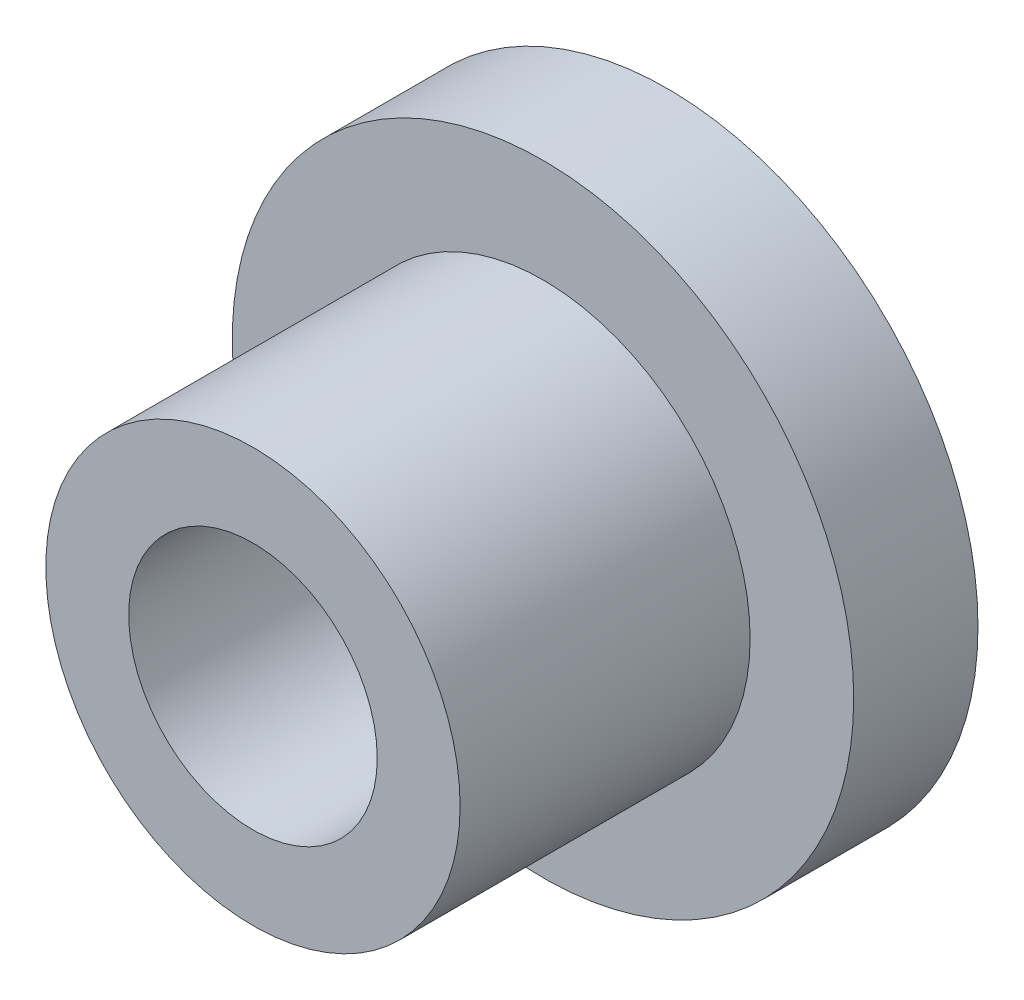
SolidWorks part; units mm, degrees
ref_plane "Ön Düzlem" through (0, 0, 0) normal (0, 0, 1) x (1, 0, 0)
ref_plane "Üst Düzlem" through (0, 0, 0) normal (0, 1, 0) x (1, 0, 0)
ref_plane "Sağ Düzlem" through (0, 0, 0) normal (1, 0, 0) x (0, 0, -1)
sketch "Çizim2" plane through (0, 0, 0) normal (1, 0, 0) x (0, 0, -1)
  line L0 (-17.5855, 0) -> (13.5614, 0) construction
  line L1 (-14.326, 10) -> (-0.326, 10)
  line L2 (-14.326, 10) -> (-14.326, 6)
  line L3 (-14.326, 6) -> (-2.8169, 6)
  line L5 (-2.8169, 6) -> (5.674, 6)
  line L6 (-0.326, 10) -> (-0.326, 15)
  line L7 (-0.326, 15) -> (5.674, 15)
  line L8 (5.674, 6) -> (5.674, 15)
  dimension "D1" = 20
  dimension "D2" = 6
  dimension "D3" = 10
  dimension "D4" = 15
  dimension "D5" = 6
revolve "Döndür1" add sketch "Çizim2" angle 360 about L0
